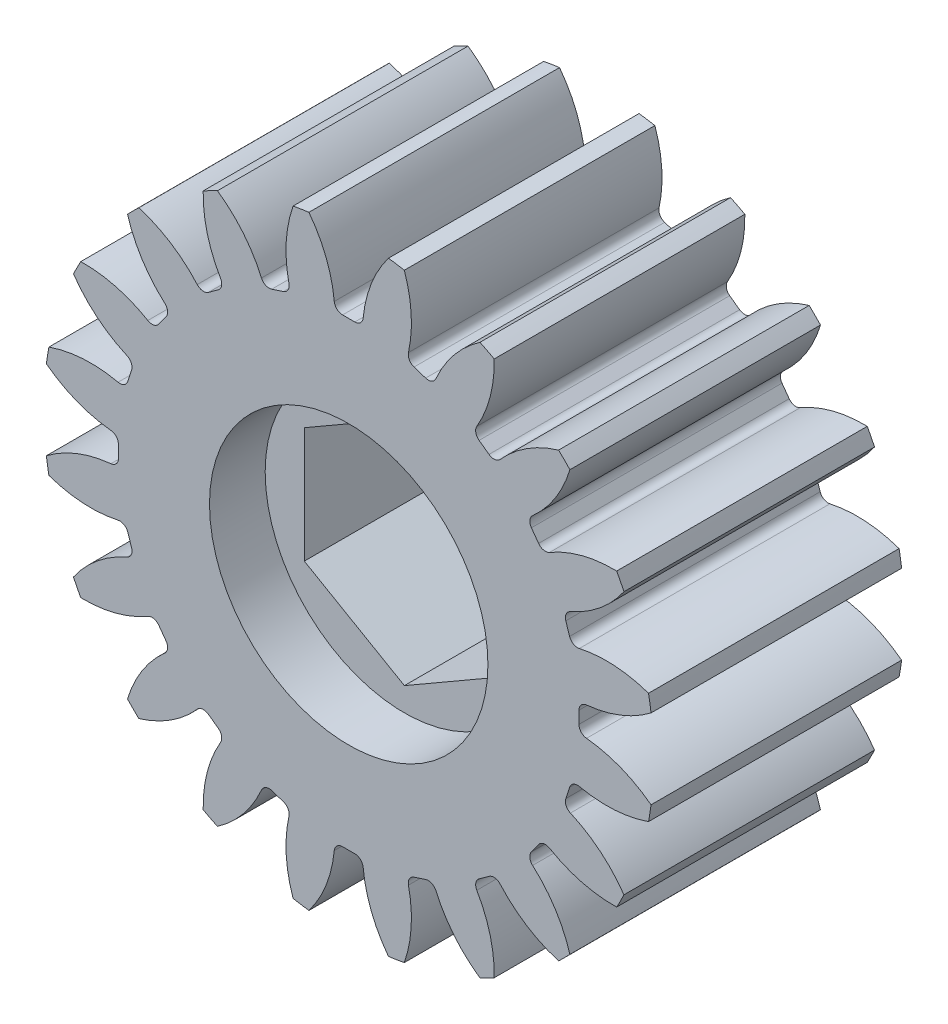
SolidWorks part; units mm, degrees
ref_plane "Ebene vorne" through (0, 0, 0) normal (0, 0, 1) x (1, 0, 0)
ref_plane "Ebene oben" through (0, 0, 0) normal (0, 1, 0) x (1, 0, 0)
ref_plane "Ebene rechts" through (0, 0, 0) normal (1, 0, 0) x (0, 0, -1)
sketch "Skizze1" plane through (0, 0, 0) normal (0, 0, 1) x (1, 0, 0)
  circle A0 centre (0, 0) radius 10.9515
  dimension "D1" = 21.903
extrude "Aufsatz-Linear austragen1" add sketch "Skizze1" along normal mid plane 9
sketch "Skizze4" plane through (0, 0, 4.5) normal (0, 0, 1) x (1, 0, 0)
  circle A0 centre (0, 0) radius 2.5
  circle A1 centre (0, 0) radius 5
  dimension "D1" = 10
  dimension "D2" = 5
extrude "Schnitt-Linear austragen2" cut sketch "Skizze4" against normal blind 2
sketch "Skizze6" plane through (0, 0, 4.5) normal (0, 0, 1) x (1, 0, 0)
  line L0 (0, 0) -> (0, 10.9515) construction
  line L1 (-0.2199, 8.27) -> (0.2199, 8.27)
  circle A0 centre (0, 0) radius 10.9515 construction
  arc A1 (0.5184, 8.5407) -> (2.08, 11.55) centre (5.0567, 8.0956) cw
  arc A2 (-0.5184, 8.5407) -> (-2.08, 11.55) centre (-5.0567, 8.0956) ccw
  arc A3 (-2.08, 11.55) -> (2.08, 11.55) centre (0, -6.3294) cw
  arc A4 (0.2199, 8.27) -> (0.5184, 8.5407) centre (0.2199, 8.57) ccw
  arc A5 (-0.5184, 8.5407) -> (-0.2199, 8.27) centre (-0.2199, 8.57) ccw
  point P13 (0, 8.27)
  point P16 (0.5, 8.27)
  point P19 (-0.5, 8.27)
  dimension "D5" = 4.56
  dimension "D6" = 18
  dimension "D7" = 0.3
  dimension "D1" = 0.5
  dimension "D2" = 8.27
  dimension "D3" = 1.58
  dimension "D4" = 3.28
extrude "Schnitt-Linear austragen3" cut sketch "Skizze6" against normal through all
pattern_circular "Kreismuster1" count 20 over 360 about axis through (0, 0, 0) along (0, 0, 1) of "Schnitt-Linear austragen3"
sketch "Skizze8" plane through (0, 0, -4.5) normal (0, 0, -1) x (-1, 0, 0)
  circle A0 centre (0, 0) radius 6
extrude "Aufsatz-Linear austragen2" add sketch "Skizze8" along normal blind 1 contours A0
sketch "Skizze7" plane through (0, 0, 4.5) normal (0, 0, 1) x (1, 0, 0)
  line L1 (0, 4.15) -> (-3.594, 2.075)
  line L2 (-3.594, 2.075) -> (-3.594, -2.075)
  line L3 (-3.594, -2.075) -> (0, -4.15)
  line L4 (0, -4.15) -> (3.594, -2.075)
  line L5 (3.594, -2.075) -> (3.594, 2.075)
  line L6 (3.594, 2.075) -> (0, 4.15)
  circle A0 centre (0, 0) radius 3.594 construction
  dimension "D1" = 8.3
extrude "Schnitt-Linear austragen4" cut sketch "Skizze7" against normal through all
